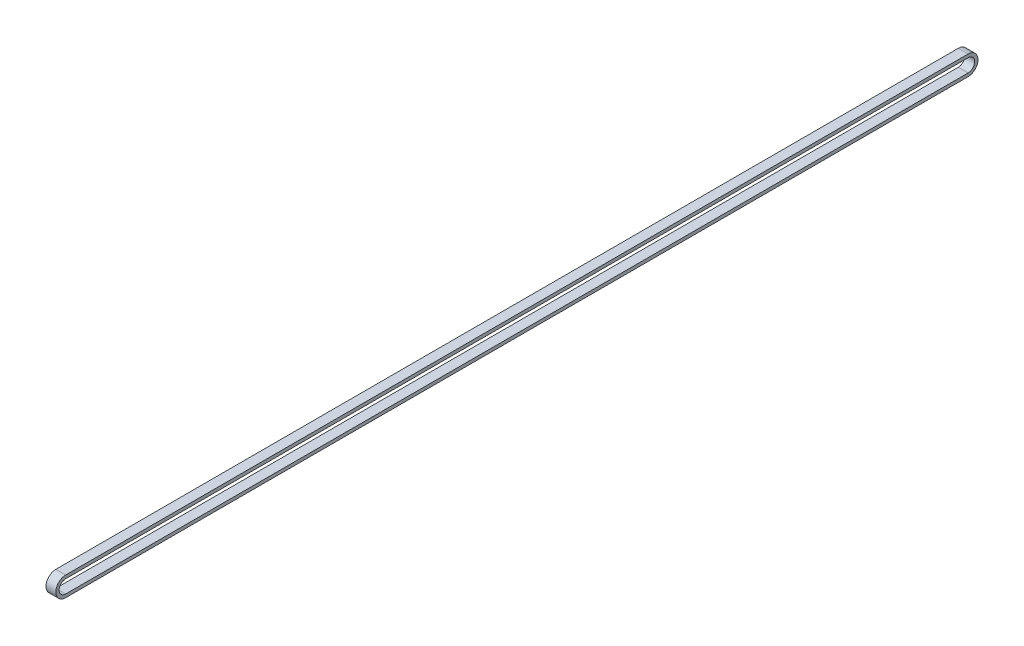
SolidWorks part; units mm, degrees
ref_plane "前视基准面" through (0, 0, 0) normal (0, 0, 1) x (1, 0, 0)
ref_plane "上视基准面" through (0, 0, 0) normal (0, 1, 0) x (1, 0, 0)
ref_plane "右视基准面" through (0, 0, 0) normal (1, 0, 0) x (0, 0, -1)
other "Configuration Table"
sketch "草图1" plane through (0, 0, 0) normal (1, 0, 0) x (0, 0, -1)
  line L0 (0, 10) -> (550, 10)
  line L1 (0, 0) -> (550, 0)
  line L3 (0, 8) -> (550, 8)
  line L5 (0, -2) -> (550, -2)
  arc A0 (0, 8) -> (0, 0) centre (0, 4) ccw
  arc A1 (550, 8) -> (550, 0) centre (550, 4) cw
  arc A2 (550, 10) -> (550, -2) centre (550, 4) cw
  arc A3 (0, 10) -> (0, -2) centre (0, 4) ccw
  dimension "D1" = 550
  dimension "D2" = 8
  dimension "D3" = 2
extrude "凸台-拉伸1" add sketch "草图1" along normal blind 6
